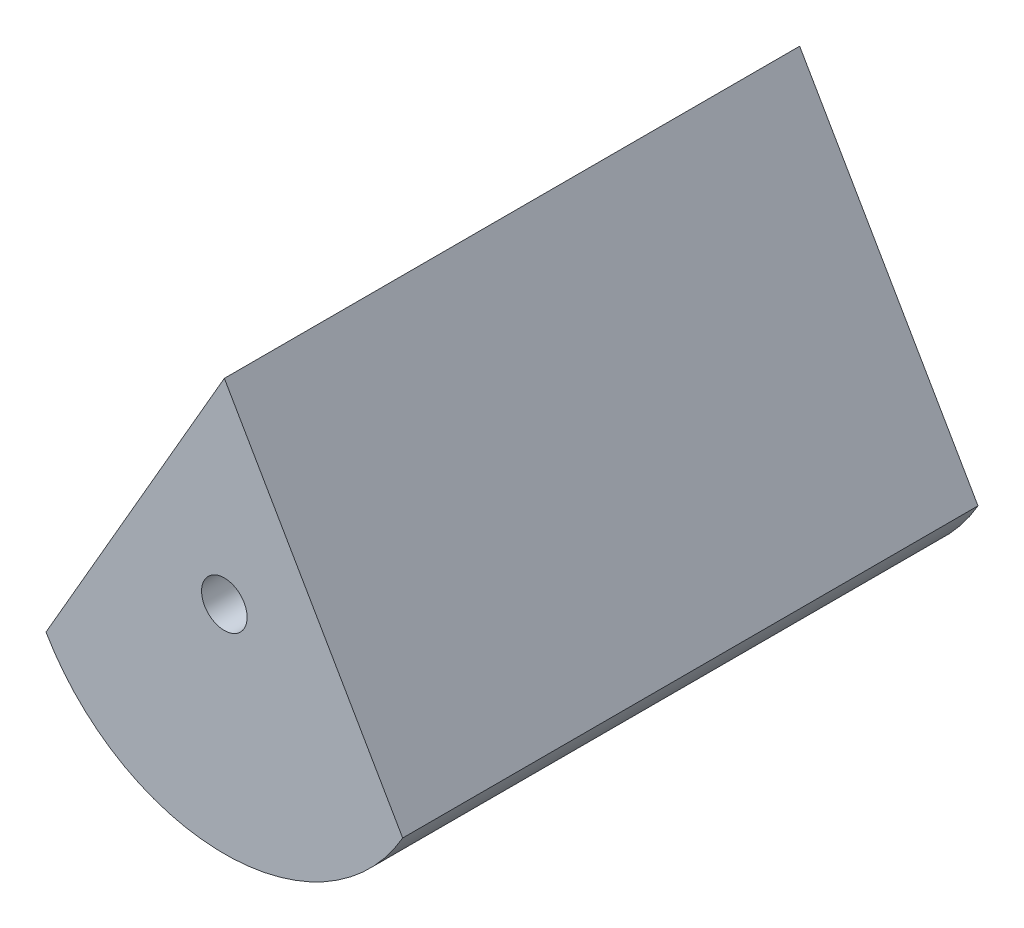
SolidWorks part; units mm, degrees
ref_plane "Ön Düzlem" through (0, 0, 0) normal (0, 0, 1) x (1, 0, 0)
ref_plane "Üst Düzlem" through (0, 0, 0) normal (0, 1, 0) x (1, 0, 0)
ref_plane "Sağ Düzlem" through (0, 0, 0) normal (1, 0, 0) x (0, 0, -1)
sketch "Çizim1" plane through (0, 0, 0) normal (0, 0, 1) x (1, 0, 0)
  line L1 (0, 17.8979) -> (-15.5, -8.9489)
  line L3 (15.5, -8.9489) -> (0, 17.8979)
  line L4 (-15.5, -8.9489) -> (15.5, -8.9489) [skipped]
  arc A1 (-15.5, -8.9489) -> (15.5, -8.9489) centre (0, 0) ccw
  dimension "D2" = 17.8979
  dimension "D1" = 31
extrude "Yükseklik-Ekstrüzyon1" add sketch "Çizim1" along normal blind 50
sketch "Çizim2" plane through (0, 0, 50) normal (0, 0, 1) x (1, 0, 0)
  circle A0 centre (0, 0.8979) radius 1.9799
  dimension "D1" = 3.9598
extrude "Kes-Ekstrüzyon1" cut sketch "Çizim2" against normal blind 50
